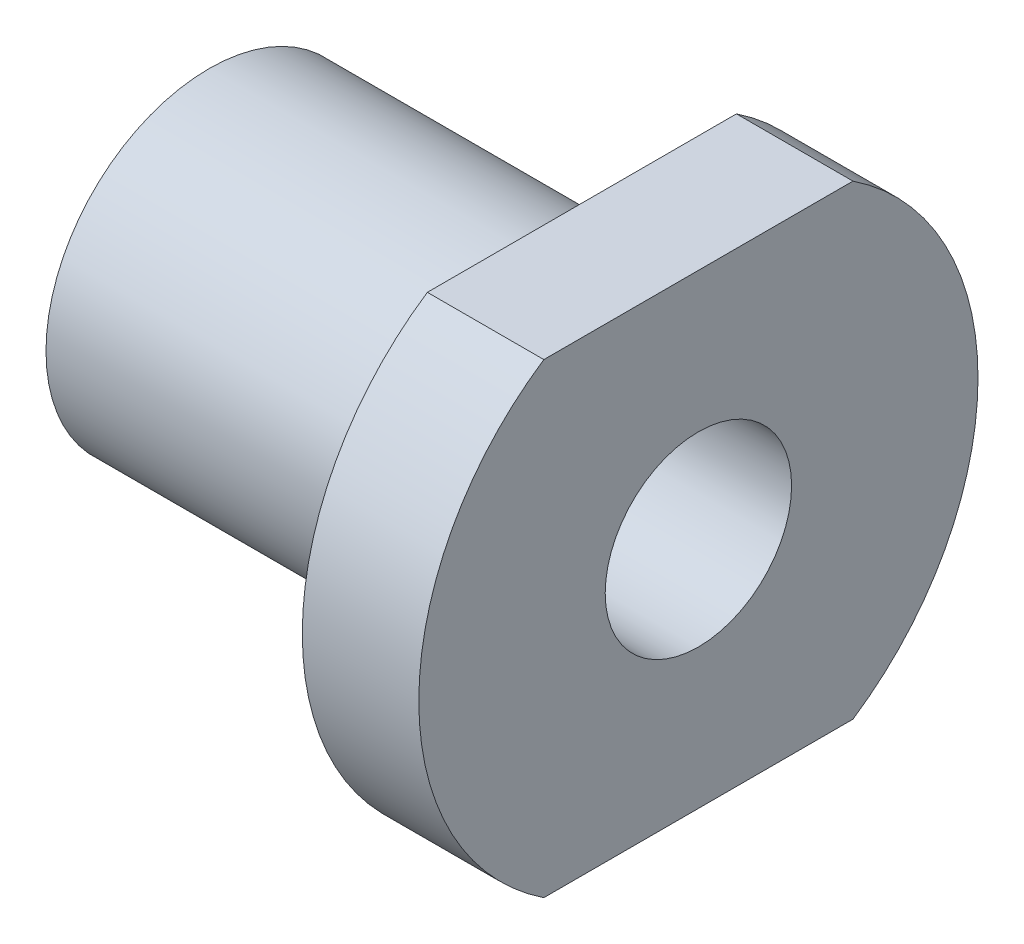
SolidWorks part; units mm, degrees
material "AISI 1020"
ref_plane "Alzado" through (0, 0, 0) normal (0, 0, 1) x (1, 0, 0)
ref_plane "Planta" through (0, 0, 0) normal (0, 1, 0) x (1, 0, 0)
ref_plane "Vista lateral" through (0, 0, 0) normal (1, 0, 0) x (0, 0, -1)
sketch "Croquis1" plane through (0, 0, 0) normal (0, 0, 1) x (1, 0, 0)
  line L0 (0, 0) -> (-52.0118, 0) construction
  line L1 (0, 8) -> (0, 24)
  line L2 (0, 24) -> (-10, 24)
  line L3 (-10, 24) -> (-10, 14)
  line L4 (-10, 14) -> (-42, 14)
  line L5 (-42, 14) -> (-42, 8)
  line L6 (-42, 8) -> (0, 8)
  dimension "D1" = 16
  dimension "D2" = 28
  dimension "D3" = 48
  dimension "D4" = 10
  dimension "D5" = 42
revolve "Revolución1" add sketch "Croquis1" angle 360 about L0
sketch "Croquis2" plane through (0, 0, 0) normal (1, 0, 0) x (0, 0, -1)
  line L1 (-30, 20) -> (30, 20)
  line L2 (-30, 20) -> (-30, -20)
  line L3 (-30, -20) -> (30, -20)
  line L4 (30, 20) -> (30, -20)
  line L5 (-30, 20) -> (30, -20) construction
  line L6 (-30, -20) -> (30, 20) construction
  point P0 (0, 0)
  dimension "D1" = 40
  dimension "D2" = 60
extrude "Cortar-Extruir1" cut sketch "Croquis2" against normal blind 10 flip side to cut
